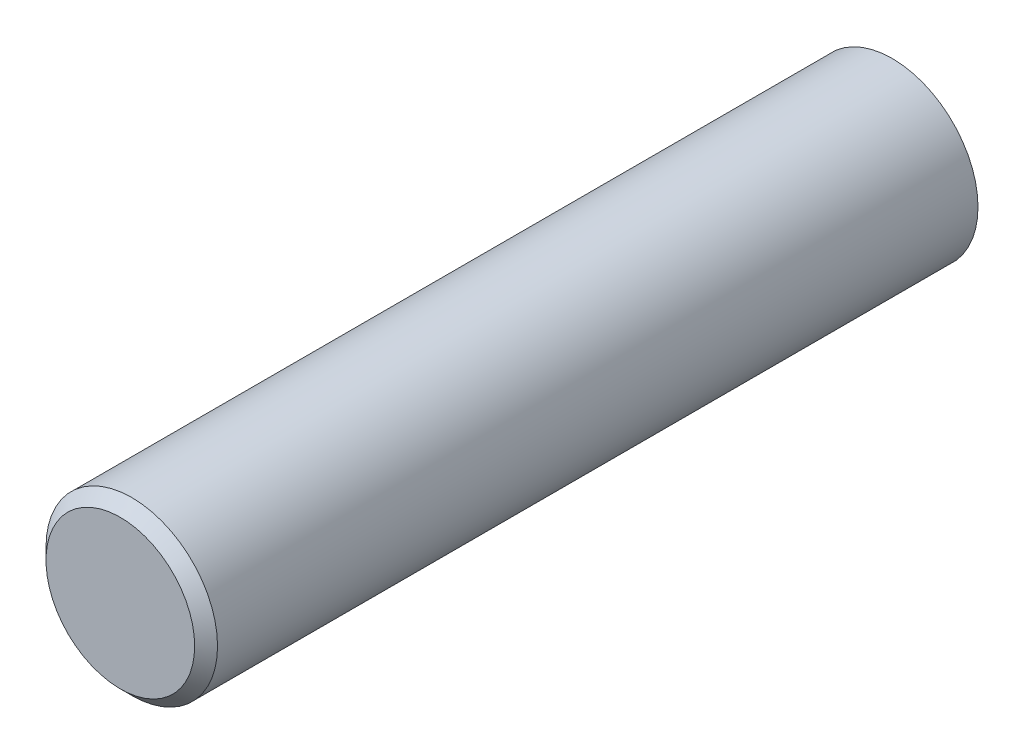
SolidWorks part; units mm, degrees
ref_plane "Front Plane" through (0, 0, 0) normal (0, 0, 1) x (1, 0, 0)
ref_plane "Top Plane" through (0, 0, 0) normal (0, 1, 0) x (1, 0, 0)
ref_plane "Right Plane" through (0, 0, 0) normal (1, 0, 0) x (0, 0, -1)
sketch "Sketch1" plane through (0, 0, 0) normal (0, 0, 1) x (1, 0, 0)
  circle A0 centre (0, 0) radius 1.5
  dimension "D1" = 3
extrude "Boss-Extrude1" add sketch "Sketch1" along normal mid plane 13.5
chamfer "Chamfer1" distance 0.2 angle 45 1 edges at (1.5, 0, 6.75)
